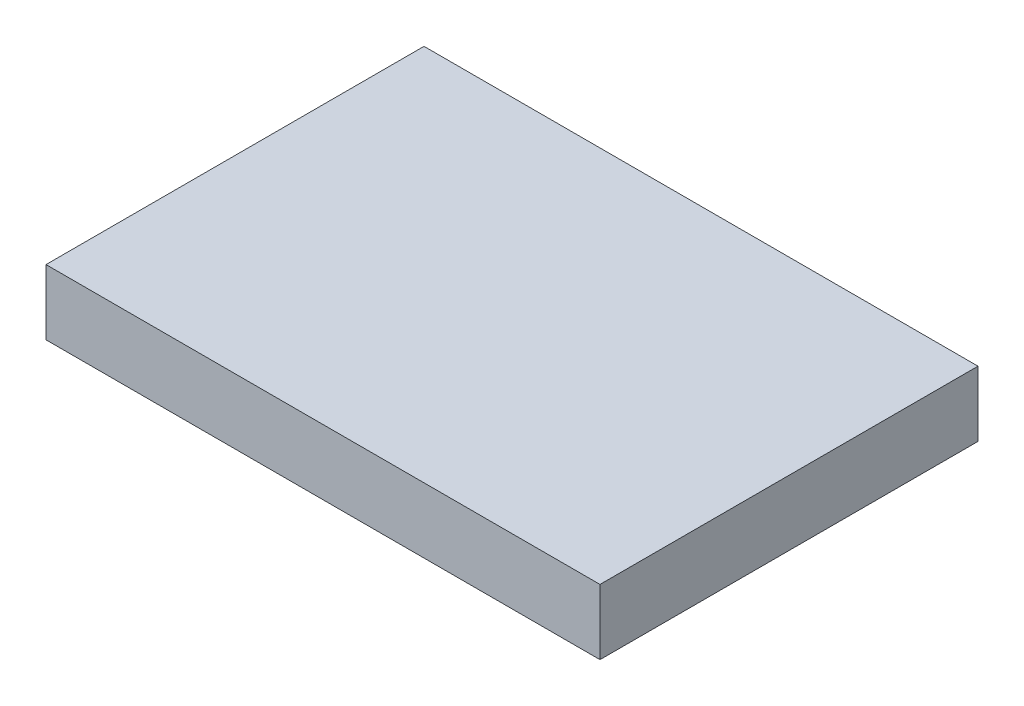
SolidWorks part; units mm, degrees
ref_plane "前视基准面" through (0, 0, 0) normal (0, 0, 1) x (1, 0, 0)
ref_plane "上视基准面" through (0, 0, 0) normal (0, 1, 0) x (1, 0, 0)
ref_plane "右视基准面" through (0, 0, 0) normal (1, 0, 0) x (0, 0, -1)
sketch "草图1" plane through (0, 0, 0) normal (0, 1, 0) x (1, 0, 0)
  line L1 (-37.4845, 15.3986) -> (47.5155, 15.3986)
  line L2 (-37.4845, 15.3986) -> (-37.4845, -42.6014)
  line L3 (-37.4845, -42.6014) -> (47.5155, -42.6014)
  line L4 (47.5155, 15.3986) -> (47.5155, -42.6014)
  dimension "D1" = 85
  dimension "D2" = 58
extrude "凸台-拉伸1" add sketch "草图1" along normal blind 10
